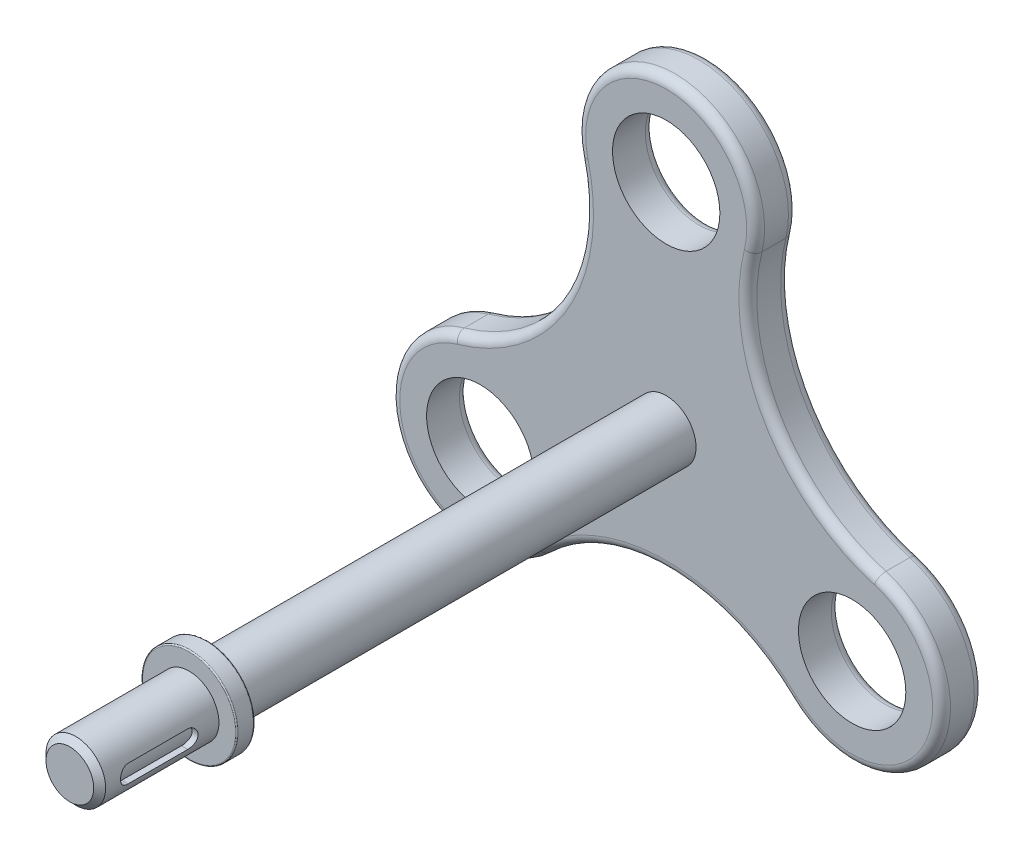
SolidWorks part; units mm, degrees
ref_plane "Front Plane" through (0, 0, 0) normal (0, 0, 1) x (1, 0, 0)
ref_plane "Top Plane" through (0, 0, 0) normal (0, 1, 0) x (1, 0, 0)
ref_plane "Right Plane" through (0, 0, 0) normal (1, 0, 0) x (0, 0, -1)
sketch "Sketch2" plane through (0, 0, 0) normal (0, 0, 1) x (1, 0, 0)
  line L0 (0, 0) -> (0, 18) construction
  line L1 (0, 0) -> (15.5885, -9) construction
  line L2 (0, 0) -> (-15.5885, -9) construction
  circle A0 centre (0, 18) radius 4.5
  circle A1 centre (-15.5885, -9) radius 4.5
  circle A2 centre (15.5885, -9) radius 4.5
  circle A3 centre (0, 18) radius 7.5 construction
  circle A4 centre (-15.5885, -9) radius 7.5 construction
  circle A5 centre (15.5885, -9) radius 7.5 construction
  arc A6 (-7.2818, 16.2042) -> (-17.6741, -1.7958) centre (-21.8455, 12.6125) cw
  arc A7 (17.6741, -1.7958) -> (7.2818, 16.2042) centre (21.8455, 12.6125) cw
  arc A8 (-10.3923, -14.4083) -> (10.3923, -14.4083) centre (0, -25.225) cw
  arc A9 (-7.2818, 16.2042) -> (7.2818, 16.2042) centre (0, 18) cw
  arc A10 (-17.6741, -1.7958) -> (-10.3923, -14.4083) centre (-15.5885, -9) ccw
  arc A11 (10.3923, -14.4083) -> (17.6741, -1.7958) centre (15.5885, -9) ccw
  circle A12 centre (0, 0) radius 2.5
  point P8 (0, 0)
  point P23 (0, 0)
  dimension "D3" = 9
  dimension "D4" = 15
  dimension "D5" = 15
  dimension "D7" = 5
  dimension "D1" = 18
  dimension "D2" = 3
  dimension "D6" = 3
extrude "Boss-Extrude1" add sketch "Sketch2" along normal mid plane 3.5 contours A8 A11 A7 A9 A6 A10 A12 A0 A1 A2
sketch "Sketch6" plane through (0, 0, -1.75) normal (0, 0, -1) x (-1, 0, 0)
  circle A0 centre (0, 0) radius 2.5 construction
  circle A1 centre (0, 0) radius 2.5
extrude "Boss-Extrude2" add sketch "Sketch6" against normal blind 53.5
fillet "Fillet1" radius 0.75 15 edges at (22.0836, -12.75, -1.75) (8.8551, 5.1125, -1.75) (0, 25.5, -1.75) (-8.8551, 5.1125, -1.75) (-22.0836, -12.75, -1.75) (0, -10.225, -1.75) (20.0885, -9, -1.75) (-11.0885, -9, -1.75) (4.5, 18, -1.75) (-22.0836, -12.75, 1.75) (-8.8551, 5.1125, 1.75) (0, 25.5, 1.75) (8.8551, 5.1125, 1.75) (22.0836, -12.75, 1.75) (0, -10.225, 1.75)
sketch "Sketch7" plane through (0, 0, 0) normal (0, 1, 0) x (1, 0, 0)
  line L0 (2.5, -51.75) -> (2.5, -1.75) construction
  line L1 (2.5, -40.25) -> (4, -40.25)
  line L2 (2.5, -40.25) -> (2.5, -41.75)
  line L3 (2.5, -41.75) -> (4, -41.75)
  line L4 (4, -40.25) -> (4, -41.75)
  line L5 (-2.5, -51.75) -> (2.5, -51.75) construction
  dimension "D1" = 1.5
  dimension "D2" = 10
revolve "Revolve1" add sketch "Sketch7" angle 360 about axis through (0, 0, 51.75) along (0, 0, -1)
sketch "Sketch8" plane through (0, 0, 0) normal (1, 0, 0) x (0, 0, -1)
  line L0 (-49.25, 0) -> (-44.25, 0) construction
  line L1 (-51.75, 0) -> (-41.75, 0) construction
  line L2 (-49.25, 0.75) -> (-44.25, 0.75)
  line L3 (-49.25, -0.75) -> (-44.25, -0.75)
  line L4 (-51.75, 2.5) -> (-51.75, -2.5) construction
  arc A0 (-49.25, 0.75) -> (-49.25, -0.75) centre (-49.25, 0) ccw
  arc A1 (-44.25, -0.75) -> (-44.25, 0.75) centre (-44.25, 0) ccw
  point P5 (-46.75, 0)
  dimension "D1" = 5
  dimension "D2" = 5
  dimension "D3" = 1.5
extrude "Cut-Extrude1" cut sketch "Sketch8" against normal offset from surface (3.146 mm away) 0.5 from offset 5
chamfer "Chamfer1" distance 0.5 angle 45 1 edges at (-2.5, 0, 51.75)
fillet "Fillet2" radius 0.1 2 edges at (4, 0, 41.75) (4, 0, 40.25)
